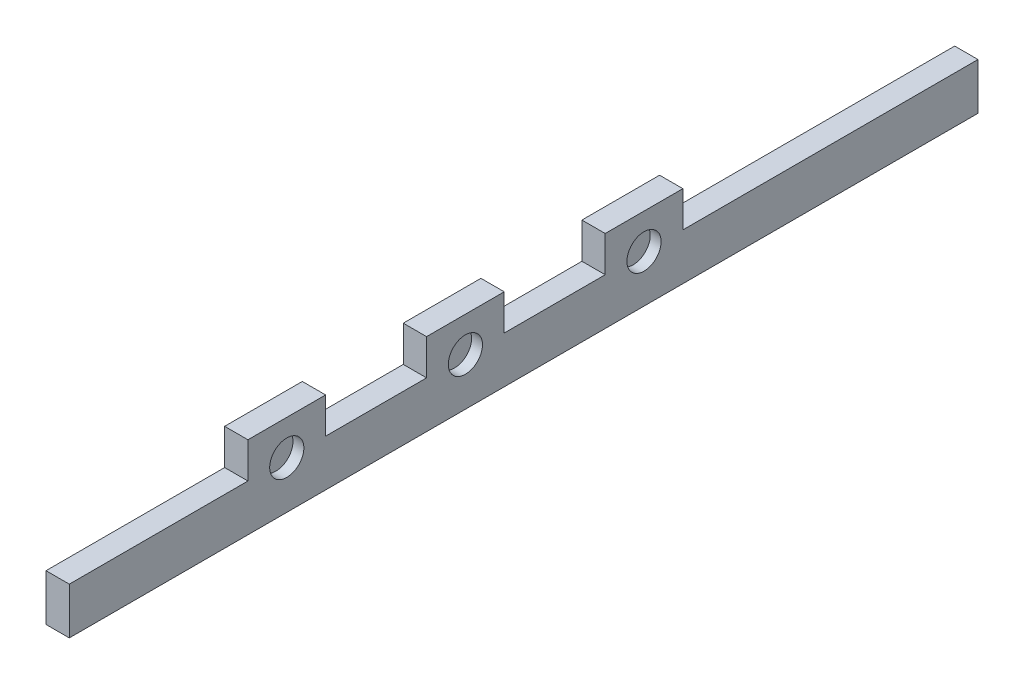
SolidWorks part; units mm, degrees
ref_plane "Alzado" through (0, 0, 0) normal (0, 0, 1) x (1, 0, 0)
ref_plane "Planta" through (0, 0, 0) normal (0, 1, 0) x (1, 0, 0)
ref_plane "Vista lateral" through (0, 0, 0) normal (1, 0, 0) x (0, 0, -1)
sketch "Croquis1" plane through (0, 0, 0) normal (1, 0, 0) x (0, 0, -1)
  line L0 (-292.5, 0) -> (292.5, 0)
  line L1 (-37.5, 30) -> (-37.5, 0) construction
  line L2 (-62.5, 30) -> (-62.5, 53)
  line L3 (-62.5, 53) -> (-12.5, 53)
  line L4 (-12.5, 30) -> (-12.5, 53)
  line L5 (102.5, 30) -> (292.5, 30)
  line L6 (-177.5, 30) -> (-177.5, 53)
  line L7 (-62.5, 30) -> (-127.5, 30)
  line L8 (-292.5, 0) -> (-292.5, 30)
  line L9 (-177.5, 53) -> (-127.5, 53)
  line L10 (-127.5, 30) -> (-127.5, 53)
  line L11 (-12.5, 30) -> (52.5, 30)
  line L12 (292.5, 0) -> (292.5, 30)
  line L13 (-62.5, 30) -> (-37.5, 30) construction
  line L14 (52.5, 30) -> (52.5, 53)
  line L15 (52.5, 53) -> (102.5, 53)
  line L16 (102.5, 30) -> (102.5, 53)
  line L17 (-177.5, 30) -> (-292.5, 30)
  point P0 (0, 0)
  dimension "D4" = 53
  dimension "D1" = 585
  dimension "D2" = 50
  dimension "D3" = 30
  dimension "D5" = 65
  dimension "D6" = 25
  dimension "D7" = 330
extrude "Saliente-Extruir1" add sketch "Croquis1" along normal blind 15
sketch "Croquis2" plane through (15, 0, 0) normal (1, 0, 0) x (0, 0, -1)
  line L0 (-177.5, 30.5) -> (-152.5, 30.5) construction
  line L1 (-177.5, 53) -> (-177.5, 30) construction
  line L2 (-62.5, 30.5) -> (-37.5, 30.5) construction
  line L3 (52.5, 30.5) -> (77.5, 30.5) construction
  line L4 (-177.5, 30) -> (-292.5, 30) construction
  line L5 (-62.5, 53) -> (-62.5, 30) construction
  line L6 (52.5, 53) -> (52.5, 30) construction
  circle A0 centre (-37.5, 30.5) radius 11
  circle A1 centre (-152.5, 30.5) radius 11
  circle A2 centre (77.5, 30.5) radius 11
  dimension "D2" = 22
  dimension "D1" = 25
  dimension "D3" = 0.5
extrude "Cortar-Extruir1" cut sketch "Croquis2" against normal blind 7
